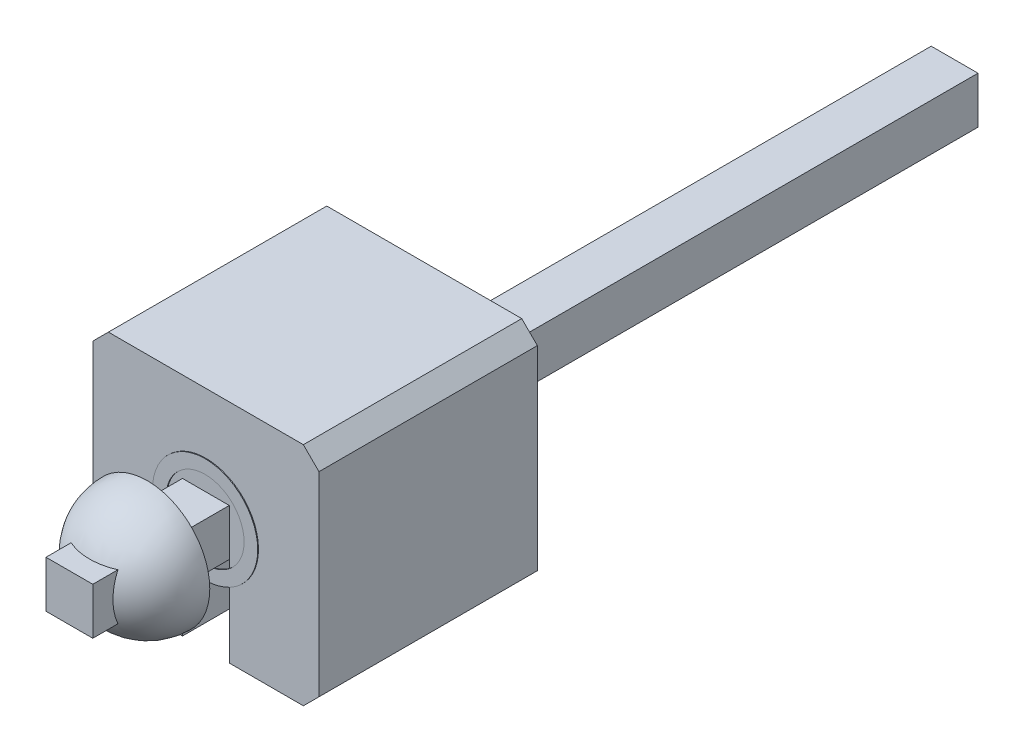
SolidWorks part; units mm, degrees
ref_plane "Plan de face" through (0, 0, 0) normal (0, 0, 1) x (1, 0, 0)
ref_plane "Plan de dessus" through (0, 0, 0) normal (0, 1, 0) x (1, 0, 0)
ref_plane "Plan de droite" through (0, 0, 0) normal (1, 0, 0) x (0, 0, -1)
sketch "Esquisse1" plane through (0, 0, 0) normal (0, 0, 1) x (1, 0, 0)
  line L0 (-1.25, 1.45) -> (-1.45, 1.25)
  line L1 (1.25, -1.45) -> (-1.25, -1.45)
  line L2 (1.45, -1.25) -> (1.45, 1.25)
  line L3 (1.25, 1.45) -> (-1.25, 1.45)
  line L4 (-1.45, -1.25) -> (-1.45, 1.25)
  line L5 (1.45, -1.45) -> (-1.45, 1.45) construction
  line L6 (1.45, 1.45) -> (-1.45, -1.45) construction
  line L7 (-1.25, -1.45) -> (-1.45, -1.25)
  line L8 (1.45, -1.25) -> (1.25, -1.45)
  line L9 (1.45, 1.25) -> (1.25, 1.45)
  line L11 (-0.3, 0.3) -> (0.3, 0.3)
  line L12 (-0.3, 0.3) -> (-0.3, -0.3)
  line L13 (-0.3, -0.3) -> (0.3, -0.3)
  line L14 (0.3, 0.3) -> (0.3, -0.3)
  line L15 (-0.3, 0.3) -> (0.3, -0.3) construction
  line L16 (-0.3, -0.3) -> (0.3, 0.3) construction
  point P0 (0, 0)
  point P14 (0, 0)
  dimension "D1" = 2.9
  dimension "D2" = 0.6
  dimension "D3" = 2.5
extrude "Boss.-Extru.1" add sketch "Esquisse1" along normal blind 2.8
sketch "Esquisse2" plane through (0, 0, 2.8) normal (0, 0, 1) x (1, 0, 0)
  line L0 (-0.3, -0.3) -> (0.3, -0.3) construction
  line L1 (-0.3, -0.3) -> (0.3, -0.3)
  line L2 (-1.25, -1.45) -> (1.25, -1.45) construction
  line L3 (-0.3, -1.45) -> (0.3, -1.45)
  line L4 (-0.3, -0.3) -> (-0.3, -1.45)
  line L5 (0.3, -0.3) -> (0.3, -1.45)
extrude "Enlèv. mat.-Extru.1" cut sketch "Esquisse2" against normal blind 1
sketch "Esquisse3" plane through (0, 0, 2.8) normal (0, 0, 1) x (1, 0, 0)
  line L0 (0.3, -0.3) -> (-0.3, -0.3) construction
  line L1 (-0.3, 0.3) -> (-0.3, -1.45) construction
  line L2 (0.3, 0.3) -> (-0.3, 0.3) construction
  line L3 (0.3, -1.45) -> (0.3, 0.3) construction
  line L4 (0.3, -0.3) -> (-0.3, -0.3)
  line L5 (-0.3, 0.3) -> (-0.3, -0.3)
  line L6 (0.3, 0.3) -> (-0.3, 0.3)
  line L7 (0.3, -0.3) -> (0.3, 0.3)
extrude "Boss.-Extru.2" add sketch "Esquisse3" along normal blind 0.75 and the other way blind 9.8
chamfer "Chanfrein1" distance 0.2 angle 45 4 edges at (0, 0.3, -7) (-0.3, 0, -7) (0, -0.3, -7) (0.3, 0, -7)
sketch "Esquisse4" plane through (0, 0, 2.8) normal (0, 0, 1) x (1, 0, 0)
  circle A0 centre (0, 0) radius 0.5
  circle A1 centre (0, 0) radius 0.6746
  dimension "D1" = 1
extrude "Boss.-Extru.3" add sketch "Esquisse4" along normal blind 0.01
sketch "Esquisse5" plane through (0, 0, 3.55) normal (0, 0, 1) x (1, 0, 0)
  line L0 (0.8, 0) -> (-0.8, 0)
  arc A0 (0.8, 0) -> (-0.8, 0) centre (0, 0) ccw
  point P6 (0, 0)
  dimension "D1" = 1.6
revolve "Révolution1" add sketch "Esquisse5" angle 180 about L0
sketch "Esquisse6" plane through (0, 0, 3.55) normal (0, 0, -1) x (-1, 0, 0)
  line L0 (0.3, 0.3) -> (0.3, -0.3) construction
  line L1 (-0.3, -0.3) -> (-0.3, 0.3) construction
  line L2 (-0.3, 0.3) -> (0.3, 0.3) construction
  line L3 (0.3, -0.3) -> (-0.3, -0.3) construction
  line L4 (0.3, 0.3) -> (0.3, -0.3)
  line L5 (0.3, -0.3) -> (-0.3, -0.3)
  line L6 (-0.3, 0.3) -> (0.3, 0.3)
  line L7 (-0.3, -0.3) -> (-0.3, 0.3)
extrude "Boss.-Extru.4" add sketch "Esquisse6" against normal blind 1
